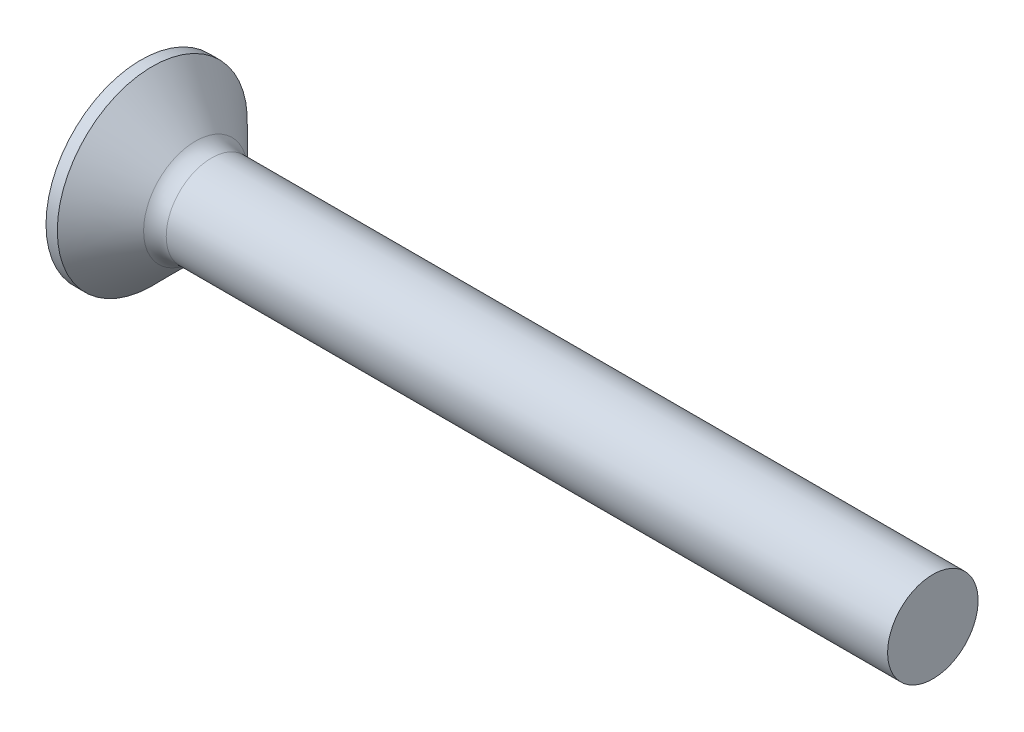
SolidWorks part; units mm, degrees
revolve "Base-Revolve" add sketch "BodySke"
sketch "BodySke" plane through (0, 0, 0) normal (0, 0, 1) x (1, 0, 0)
  line L0 (0, 0) -> (0, 4.2)
  line L1 (0, 4.2) -> (0.5, 4.2)
  line L2 (2.7, 2) -> (35, 2)
  line L3 (35, 2) -> (35, 0)
  line L4 (35, 0) -> (0, 0)
  line L5 (-6.35, 0) -> (82.55, 0) construction
  line L6 (2.7, -2) -> (35, -2) construction
  line L7 (0.5, -4.2) -> (2.7, -2) construction
  line L8 (0.5, 4.2) -> (2.7, 2)
  line L9 (0, -4.2) -> (0.5, -4.2) construction
  line L10 (3.4, 3.5875) -> (3.4, -5.9375) construction
  line L11 (0, 6.35) -> (0, -3.175) construction
  dimension "Diameter" = 4
  dimension "Length" = 35
  dimension "Head_ht" = 2.7
  dimension "Head_dia" = 8.4
  dimension "Head_ang" = 90
  dimension "D6" = 0.5
  dimension "Advance" = 0.7
  dimension "Thread_nom" = 35
cosmetic thread "ThreadCosmetic" [suppressed]
fillet "Fillet1" radius 1 1 edges at (2.7, 0, 2)
ref_plane "Plane1" through (0, 0, 0) normal (0, 0, 1) x (1, 0, 0)
ref_plane "Plane2" through (0, 0, 0) normal (0, 1, 0) x (1, 0, 0)
ref_plane "Plane3" through (0, 0, 0) normal (1, 0, 0) x (0, 0, -1)
other "Configuration Table"
sketch "Sketch3" plane through (0, 0, 0) normal (-1, 0, 0) x (0, 0, 1)
  line L0 (-0.515, 2.2) -> (0.515, 2.2)
  line L1 (0.515, 2.2) -> (0.515, -2.2)
  line L2 (0.515, -2.2) -> (-0.515, -2.2)
  line L3 (-0.515, -2.2) -> (-0.515, 2.2)
  dimension "Cross_dia" = 4.4
  dimension "Cross_width" = 1.03
  dimension "D1" = 2.2
  dimension "D2" = 0.515
ref_plane "Plane4" through (2.51, 0, 0) normal (-1, 0, 0) x (0, 0, 1)
sketch "Sketch4" plane through (2.51, 0, 0) normal (-1, 0, 0) x (0, 0, 1)
  line L0 (-0.515, 0.9486) -> (0.515, 0.9486)
  line L3 (0.515, 0.9486) -> (0.515, -0.9486)
  line L4 (0.515, -0.9486) -> (-0.515, -0.9486)
  line L5 (-0.515, -0.9486) -> (-0.515, 0.9486)
  dimension "D2" = 1.8971
  dimension "D1" = 1.03
  dimension "D4" = 0.9486
  dimension "D3" = 0.515
loft "Recess" cut profiles "Sketch3", "Sketch4"
pattern_circular "RecPat" count 2 every 90 about axis through (0, 0, 0) along (1, 0, 0) of "Recess"
sketch "RecCorSke" plane through (0, 0, 0) normal (0, 0, 1) x (1, 0, 0)
  line L0 (-3.175, 0) -> (15.875, 0) construction
  line L2 (0, 0) -> (0, 1.0265)
  line L3 (0, 1.0265) -> (2.51, 0.851)
  line L4 (2.51, 0.851) -> (2.7865, 0)
  line L5 (2.7865, 0) -> (0, 0)
  dimension "Diameter" = 1.702
  dimension "Depth" = 2.51
  dimension "Draft_angle" = 4
  dimension "Bottom_angle" = 18
revolve "RecessCore" cut sketch "RecCorSke" angle 360 about L0
sketch "ThdSchSke" plane through (0, 0, 0) normal (0, 0, 1) x (1, 0, 0)
  line L0 (3.4, -1.61) -> (3.1269, -2)
  line L1 (3.4, -1.61) -> (3.6731, -2)
  line L2 (3.6731, -2) -> (3.6731, -2.5)
  line L3 (-3.175, 0) -> (5.1513, 0) construction
  line L5 (3.6731, -2.5) -> (3.1269, -2.5)
  line L6 (3.1269, -2.5) -> (3.1269, -2)
  line L7 (0, 4.2) -> (0, -4.2) construction
  dimension "Diameter" = 4
  dimension "Thread_minor" = 3.22
  dimension "Start" = 3.4
revolve "ThreadSchematic" [suppressed] cut sketch "ThdSchSke" angle 360 about L3
pattern_linear "ThdSchPat" [suppressed]
equation "\"D1@Sketch3\" = \"Cross_dia@Sketch3\" / 2"
equation "\"D2@Sketch3\" = \"Cross_width@Sketch3\" / 2"
equation "\"Depth@RecCorSke\" = \"Cross_depth@Plane4\""
equation "\"D1@Sketch4\" = \"Cross_width@Sketch3\""
equation "\"D2@Sketch4\" = \"Cross_dia@Sketch3\" - 2.0 * \"Cross_depth@Plane4\" * tan(26.5  * 0.017453292)"
equation "\"D3@Sketch4\" = \"D1@Sketch4\" / 2"
equation "\"D4@Sketch4\" = \"D2@Sketch4\" / 2"
equation "\"Thread_length@ThreadCosmetic\" = ((sgn( (\"Length@BodySke\" - \"Advance@BodySke\" * 1.0 - \"Head_ht@BodySke\" ) - \"Thread_nom@BodySke\" )-1)*( (\"Length@BodySke\" - \"Advance@BodySke\" * 1.0 - \"Head_ht@BodySke\" ) - \"Thread_nom@BodySke\" ))/-2+ \"Thread_nom@BodySke\""
equation "\"Thread_minor@ThdSchSke\" = \"Thread_minor@ThreadCosmetic\""
equation "\"Diameter@ThdSchSke\" = \"Diameter@BodySke\""
equation "\"Overcut@ThdSchSke\" = \"Diameter@BodySke\" * 1.25"
equation "\"Start@ThdSchSke\" = 0.000001 + \"Length@BodySke\" - \"Thread_length@ThreadCosmetic\"  '---Countersunk---"
equation "\"Num_threads@ThdSchPat\" = int( \"Thread_length@ThreadCosmetic\" / \"Advance@BodySke\" + 0.999 )  + 1"
equation "\"Advance@ThdSchPat\" = \"Thread_length@ThreadCosmetic\" /  (\"Num_threads@ThdSchPat\" - 1) 'relax it"
